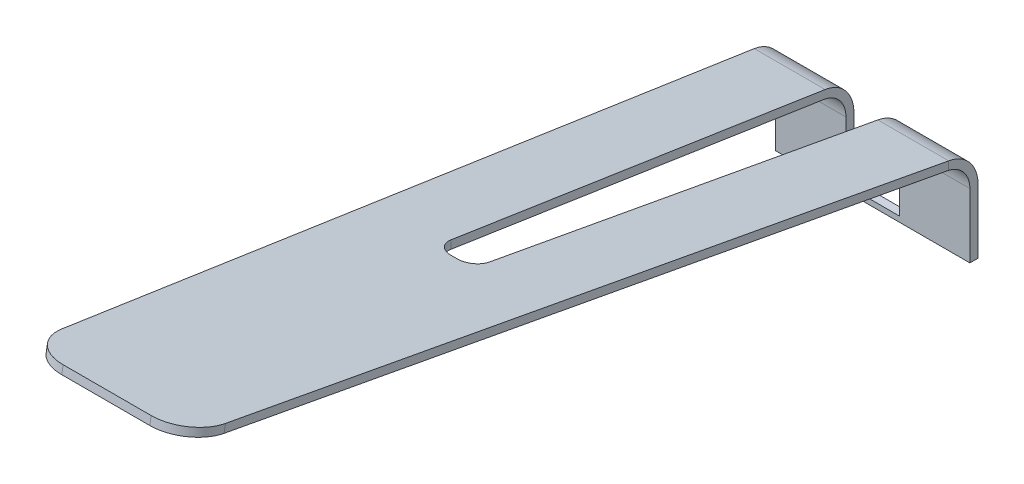
SolidWorks part; units mm, degrees
ref_plane "Спереди" through (0, 0, 0) normal (0, 0, 1) x (1, 0, 0)
ref_plane "Сверху" through (0, 0, 0) normal (0, 1, 0) x (1, 0, 0)
ref_plane "Справа" through (0, 0, 0) normal (1, 0, 0) x (0, 0, -1)
ref_plane "Плоскость4" through (2.85, 0, 0) normal (1, 0, 0) x (0, 0, -1)
sketch "Short" plane through (2.85, 0, 0) normal (1, 0, 0) x (0, 0, -1)
  line L0 (5.55, 4.85) -> (5.55, 6.0428)
  line L1 (5.1328, 6.5359) -> (-8.65, 8.85)
  line L2 (5.8, 4.95) -> (5.3, 4.95) construction
  line L3 (5.3, 4.85) -> (5.8, 4.85) construction
  arc A0 (5.55, 6.0428) -> (5.1328, 6.5359) centre (5.05, 6.0428) ccw
  point P8 (5.55, 4.95)
  dimension "D3" = 0.5
  dimension "D1" = 14.2
  dimension "D2" = 10.4
extrude "Short_Lever" add sketch "Short" along normal blind 1.8 and the other way blind 1.8 thin
sketch "Эскиз2" plane through (0, 4.95, 0) normal (0, 1, 0) x (1, 0, 0)
  line L0 (1.35, -8.65) -> (4.35, -8.65) construction
  line L3 (2.85, -3.3) -> (2.85, 3.3) construction
  line L4 (1.05, 5.1576) -> (1.35, -8.65)
  line L5 (1.05, -8.65) -> (4.65, -8.65) construction
  line L6 (1.05, 5.1576) -> (1.05, -8.65)
  line L7 (1.05, -8.65) -> (1.35, -8.65)
  line L8 (2.85, 6.4) -> (2.85, -11.133) construction
  line L9 (5.7, 6.4) -> (0, 6.4) construction
  line L10 (4.65, 5.1576) -> (4.65, -8.65)
  line L11 (4.65, 5.1576) -> (4.35, -8.65)
  line L12 (4.65, -8.65) -> (4.35, -8.65)
  line L13 (2.35, 5.8) -> (3.35, 5.8)
  line L14 (4.65, 5.8) -> (1.05, 5.8) construction
  line L15 (2.7944, -2.2) -> (2.9056, -2.2)
  line L16 (2.4945, -1.9056) -> (2.35, 5.8)
  line L17 (3.2055, -1.9056) -> (3.35, 5.8)
  arc A0 (2.9056, -2.2) -> (3.2055, -1.9056) centre (2.9056, -1.9) ccw
  arc A1 (2.7944, -2.2) -> (2.4945, -1.9056) centre (2.7944, -1.9) cw
  point P5 (2.85, -8.65)
  point P22 (2.85, 5.8)
  point P25 (2.85, -2.2)
  point P27 (3.2, -2.2)
  point P30 (2.5, -2.2)
  dimension "D5" = 0.3
  dimension "D1" = 3
  dimension "D2" = 8
  dimension "D3" = 1
  dimension "D4" = 0.7
extrude "Lever_Cut" cut sketch "Эскиз2" along normal up to vertex (4.0479 mm away) up to point (1.05, 8.9979, 8.6252)
fillet "Скругление1" radius 0.7 2 edges at (4.3503, 8.924, 8.6376) (1.3497, 8.924, 8.6376)
